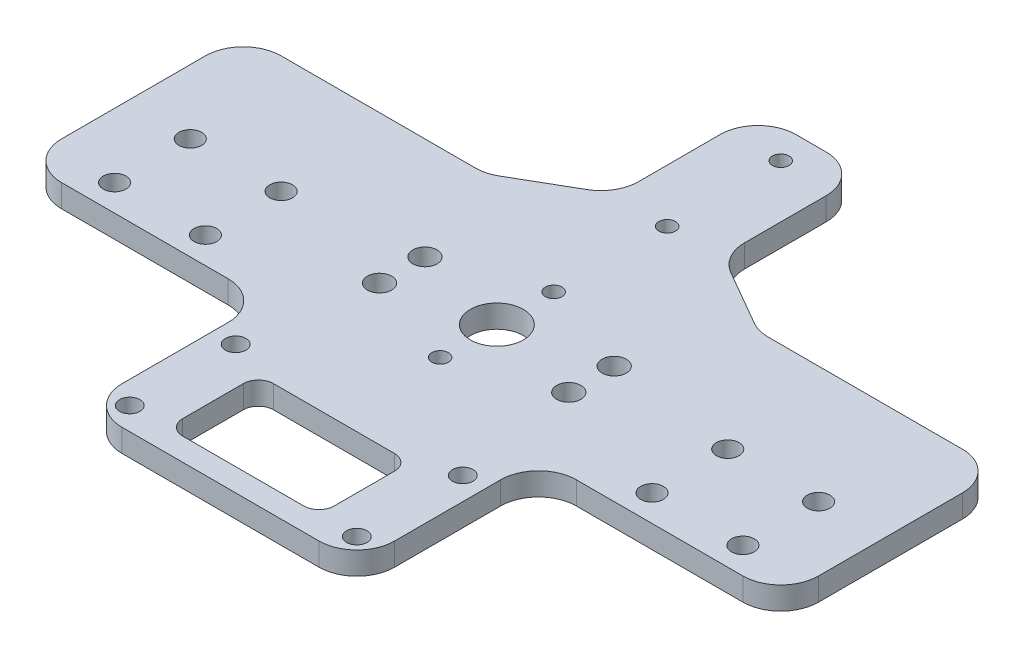
SolidWorks part; units mm, degrees
material "碳纤维"
ref_plane "前视基准面" through (0, 0, 0) normal (0, 0, 1) x (1, 0, 0)
ref_plane "上视基准面" through (0, 0, 0) normal (0, 1, 0) x (1, 0, 0)
ref_plane "右视基准面" through (0, 0, 0) normal (1, 0, 0) x (0, 0, -1)
sketch "草图1" plane through (0, 0, 0) normal (0, 1, 0) x (1, 0, 0)
  line L0 (18, 78) -> (18, 0) construction
  line L1 (0, 0) -> (36, 0)
  line L2 (-32, 29) -> (-32, 53)
  line L3 (11, 78) -> (25, 78)
  line L4 (68, 29) -> (68, 53)
  line L7 (0, 53) -> (-32, 53)
  line L8 (36, 53) -> (68, 53)
  line L9 (-32, 29) -> (0, 29) construction
  line L10 (0, 29) -> (0, 0) construction
  line L11 (36, 29) -> (36, 0) construction
  line L12 (68, 29) -> (36, 29) construction
  line L13 (0, 53) -> (0, 29) construction
  line L14 (11, 78) -> (11, 59.3509)
  line L15 (25, 78) -> (25, 59.3509)
  line L16 (11, 59.3509) -> (0, 53)
  line L17 (25, 59.3509) -> (36, 53)
  line L18 (36, 53) -> (36, 29) construction
  line L19 (0, 10) -> (36, 10) construction
  line L23 (8, 15) -> (28, 15)
  line L24 (8, 15) -> (8, 3)
  line L25 (8, 3) -> (28, 3)
  line L26 (28, 15) -> (28, 3)
  line L27 (8, 15) -> (28, 3) construction
  line L28 (8, 3) -> (28, 15) construction
  line L31 (-32, 29) -> (-32, 24)
  line L32 (-32, 24) -> (0, 24)
  line L34 (0, 24) -> (0, 0)
  line L35 (36, 24) -> (36, 0)
  line L36 (68, 24) -> (36, 24)
  line L37 (68, 29) -> (68, 24)
  circle A0 centre (3, 3) radius 1.35
  circle A1 centre (3, 17) radius 1.35
  circle A2 centre (33, 3) radius 1.35
  circle A3 centre (33, 17) radius 1.35
  circle A4 centre (18, 74) radius 1.1
  circle A5 centre (18, 59) radius 1.1
  circle A6 centre (18, 44) radius 1.1
  circle A7 centre (18, 29) radius 1.1
  circle A8 centre (18, 36.5) radius 3.5
  point P37 (18, 9)
  dimension "D9" = 2.7
  dimension "D10" = 14
  dimension "D11" = 30
  dimension "D12" = 2.2
  dimension "D13" = 4
  dimension "D15" = 15
  dimension "D16" = 7
  dimension "D18" = 9
  dimension "D19" = 20
  dimension "D1" = 100
  dimension "D2" = 78
  dimension "D3" = 36
  dimension "D4" = 25
  dimension "D5" = 24
  dimension "D6" = 14
  dimension "D7" = 150
  dimension "D8" = 10
  dimension "D17" = 36.5
  dimension "D20" = 12
  dimension "D21" = 5
  dimension "D14" = 4
extrude "凸台-拉伸1" add sketch "草图1" along normal blind 3
fillet "圆角1" radius 5 14 edges at (25, 1.5, -78) (11, 1.5, -78) (36, 1.5, -53) (25, 1.5, -59.3509) (11, 1.5, -59.3509) (0, 1.5, -53) (68, 1.5, -53) (-32, 1.5, -53) (68, 1.5, -24) (36, 1.5, -24) (36, 1.5, 0) (0, 1.5, 0) (0, 1.5, -24) (-32, 1.5, -24)
sketch "草图2" plane through (0, 3, 0) normal (0, 1, 0) x (1, 0, 0)
  line L0 (20, 78) -> (16, 78) construction
  line L1 (-21, 43.9) -> (-21, 46) construction
  line L2 (-32, 46) -> (68, 46) construction
  line L3 (-32, 48) -> (-32, 29) construction
  line L4 (68, 29) -> (68, 48) construction
  line L5 (-17.05, 46) -> (-17.05, 43.9) construction
  line L6 (-26, 46) -> (-16, 46) construction
  line L7 (-26, 46) -> (-26, 43.9) construction
  line L8 (-26, 43.9) -> (-16, 43.9) construction
  line L9 (-16, 46) -> (-16, 43.9) construction
  line L10 (-23.9, 46) -> (-18.1, 46) construction
  line L11 (-18.1, 43.9) -> (-23.9, 43.9) construction
  line L24 (18, 78) -> (18, 46) construction
  line L25 (3.9, 43.9) -> (-1.9, 43.9) construction
  line L26 (-4, 46) -> (-4, 43.9) construction
  line L27 (-1.9, 46) -> (3.9, 46) construction
  line L28 (6, 46) -> (6, 43.9) construction
  line L29 (30, 46) -> (30, 43.9) construction
  line L30 (37.9, 46) -> (32.1, 46) construction
  line L31 (40, 46) -> (40, 43.9) construction
  line L32 (32.1, 43.9) -> (37.9, 43.9) construction
  line L33 (52, 46) -> (52, 43.9) construction
  line L34 (59.9, 46) -> (54.1, 46) construction
  line L35 (62, 46) -> (62, 43.9) construction
  line L36 (54.1, 43.9) -> (59.9, 43.9) construction
  line L37 (-5.9, 23) -> (-5.9, 21) construction
  line L38 (-8, 19) -> (-5.9, 19) construction
  line L39 (-8, 23) -> (-8, 21) construction
  line L40 (-8, 25) -> (-5.9, 25) construction
  line L41 (-5.9, 37) -> (-5.9, 35) construction
  line L42 (-8, 33) -> (-5.9, 33) construction
  line L43 (-8, 37) -> (-8, 35) construction
  line L44 (-8, 39) -> (-5.9, 39) construction
  line L53 (44, 25) -> (41.9, 25) construction
  line L54 (44, 23) -> (44, 21) construction
  line L55 (44, 39) -> (41.9, 39) construction
  line L56 (41.9, 37) -> (41.9, 35) construction
  line L57 (44, 37) -> (44, 35) construction
  line L58 (44, 33) -> (41.9, 33) construction
  line L59 (68, 29) -> (68, 48) construction
  line L60 (44, 39) -> (44, 33) construction
  line L61 (44, 21) -> (44, 19) construction
  line L62 (63, 53) -> (37.3397, 53) construction
  line L63 (44, 36) -> (41.9, 36) construction
  line L64 (44, 19) -> (41.9, 19) construction
  line L65 (41.9, 23) -> (41.9, 21) construction
  line L66 (18, 36.5) -> (25.2855, 36.5) construction
  line L67 (41.9, 37) -> (41.9, 39) construction
  line L68 (41.9, 35) -> (41.9, 33) construction
  line L69 (41.9, 21) -> (41.8956, 20) construction
  line L70 (41.8956, 20) -> (41.9, 19) construction
  arc A0 (-16, 46) -> (-18.1, 46) centre (-17.05, 46) ccw construction
  arc A1 (-18.1, 43.9) -> (-16, 43.9) centre (-17.05, 43.9) ccw construction
  arc A2 (-23.9, 43.9) -> (-26, 43.9) centre (-24.95, 43.9) cw construction
  arc A3 (-26, 46) -> (-23.9, 46) centre (-24.95, 46) cw construction
  arc A16 (-1.9, 43.9) -> (-4, 43.9) centre (-2.95, 43.9) cw construction
  arc A17 (-4, 46) -> (-1.9, 46) centre (-2.95, 46) cw construction
  arc A18 (6, 46) -> (3.9, 46) centre (4.95, 46) ccw construction
  arc A19 (3.9, 43.9) -> (6, 43.9) centre (4.95, 43.9) ccw construction
  arc A20 (32.1, 43.9) -> (30, 43.9) centre (31.05, 43.9) cw construction
  arc A21 (30, 46) -> (32.1, 46) centre (31.05, 46) cw construction
  arc A22 (40, 46) -> (37.9, 46) centre (38.95, 46) ccw construction
  arc A23 (37.9, 43.9) -> (40, 43.9) centre (38.95, 43.9) ccw construction
  arc A24 (54.1, 43.9) -> (52, 43.9) centre (53.05, 43.9) cw construction
  arc A25 (52, 46) -> (54.1, 46) centre (53.05, 46) cw construction
  arc A26 (62, 46) -> (59.9, 46) centre (60.95, 46) ccw construction
  arc A27 (59.9, 43.9) -> (62, 43.9) centre (60.95, 43.9) ccw construction
  arc A36 (44, 37) -> (44, 39) centre (44, 38) ccw construction
  arc A37 (41.9, 39) -> (41.9, 37) centre (41.9, 38) ccw construction
  arc A38 (44, 33) -> (44, 35) centre (43.9956, 34) ccw construction
  arc A39 (41.9, 35) -> (41.9, 33) centre (41.8956, 34) ccw construction
  arc A44 (44, 23) -> (44, 25) centre (44, 24) ccw construction
  arc A45 (44, 19) -> (44, 21) centre (43.9956, 20) ccw construction
  arc A46 (41.9, 21) -> (41.9, 19) centre (41.8956, 20) ccw construction
  arc A47 (41.9, 25) -> (41.9, 23) centre (41.9, 24) ccw construction
  arc A48 (-5.9, 21) -> (-5.9, 19) centre (-5.8956, 20) cw construction
  arc A49 (-8, 19) -> (-8, 21) centre (-7.9956, 20) cw construction
  arc A50 (-8, 23) -> (-8, 25) centre (-8, 24) cw construction
  arc A51 (-5.9, 25) -> (-5.9, 23) centre (-5.9, 24) cw construction
  arc A52 (-5.9, 35) -> (-5.9, 33) centre (-5.8956, 34) cw construction
  arc A53 (-8, 33) -> (-8, 35) centre (-7.9956, 34) cw construction
  arc A54 (-8, 37) -> (-8, 39) centre (-8, 38) cw construction
  arc A55 (-5.9, 39) -> (-5.9, 37) centre (-5.9, 38) cw construction
  circle A58 centre (5.5, 39.5) radius 1.6
  circle A59 centre (5.5, 33.5) radius 1.6
  circle A60 centre (30.5, 33.5) radius 1.6
  circle A61 centre (30.5, 39.5) radius 1.6
  dimension "D9" = 1
  dimension "D15" = 3.2
  dimension "D8" = 2.1
  dimension "D12" = 2.1
  dimension "D18" = 2.1
  dimension "D1" = 32
  dimension "D2" = 2.1
  dimension "D3" = 10
  dimension "D5" = 6
  dimension "D6" = 12
  dimension "D7" = 24
  dimension "D10" = 6
  dimension "D11" = 14
  dimension "D14" = 28
  dimension "D16" = 6
  dimension "D17" = 12.5
  dimension "D4" = 2
  dimension "D13" = 2
extrude "切除-拉伸1" cut sketch "草图2" against normal through all
fillet "圆角2" radius 2 4 edges at (28, 1.5, -15) (8, 1.5, -3) (28, 1.5, -3) (8, 1.5, -15)
sketch "草图4" plane through (0, 3, 0) normal (0, 1, 0) x (1, 0, 0)
  circle A0 centre (-23.5, 37.5) radius 1.5 construction
  circle A1 centre (-23.5, 27.5) radius 1.5 construction
  circle A2 centre (-11.5, 37.5) radius 1.5 construction
  circle A3 centre (-11.5, 27.5) radius 1.5 construction
  circle A4 centre (47.5, 27.5) radius 1.5 construction
  circle A5 centre (47.5, 37.5) radius 1.5 construction
  circle A6 centre (59.5, 37.5) radius 1.5 construction
  circle A7 centre (59.5, 27.5) radius 1.5 construction
  circle A8 centre (-23.5, 37.5) radius 1.5
  circle A9 centre (-23.5, 27.5) radius 1.5
  circle A10 centre (-11.5, 37.5) radius 1.5
  circle A11 centre (-11.5, 27.5) radius 1.5
  circle A12 centre (47.5, 27.5) radius 1.5
  circle A13 centre (47.5, 37.5) radius 1.5
  circle A14 centre (59.5, 37.5) radius 1.5
  circle A15 centre (59.5, 27.5) radius 1.5
extrude "切除-拉伸3" cut sketch "草图4" against normal through all
